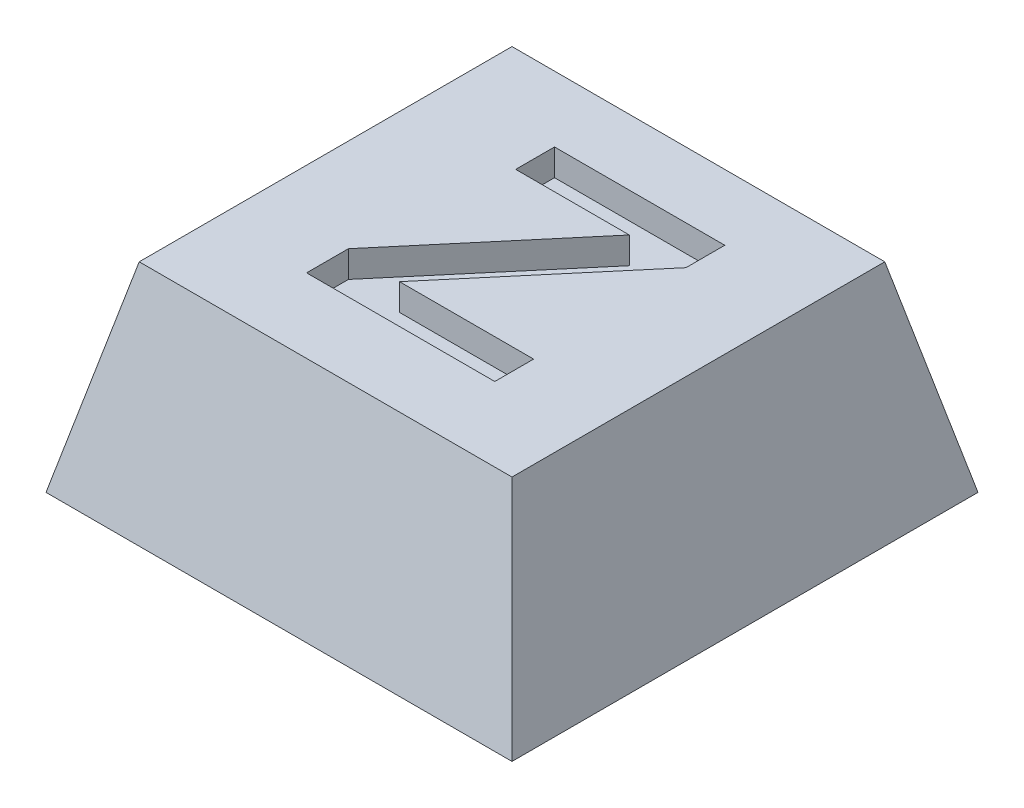
SolidWorks part; units mm, degrees
ref_plane "Front Plane" through (0, 0, 0) normal (0, 0, 1) x (1, 0, 0)
ref_plane "Top Plane" through (0, 0, 0) normal (0, 1, 0) x (1, 0, 0)
ref_plane "Right Plane" through (0, 0, 0) normal (1, 0, 0) x (0, 0, -1)
sketch "Sketch1" plane through (0, 0, 0) normal (0, 1, 0) x (1, 0, 0)
  line L1 (0, 0) -> (7, 0)
  line L2 (0, 0) -> (0, 7)
  line L3 (0, 7) -> (7, 7)
  line L4 (7, 0) -> (7, 7)
  dimension "D1" = 7
  dimension "D2" = 7
extrude "Boss-Extrude1" add sketch "Sketch1" along normal blind 3
sketch "Sketch2" plane through (0, 0, 0) normal (0, 0, 1) x (1, 0, 0)
  line L0 (0, 0) -> (0.7, 3)
  line L1 (0, 3) -> (7, 3) construction
  line L2 (0.7, 3) -> (0, 3)
  line L3 (0, 3) -> (0, 0)
  line L4 (7, 0) -> (6.3, 3)
  line L5 (6.3, 3) -> (7, 3)
  line L6 (7, 3) -> (7, 0)
  dimension "D1" = 0.7
  dimension "D2" = 0.7
extrude "Cut-Extrude1" cut sketch "Sketch2" against normal blind 7
sketch "Sketch3" plane through (0, 0, 0) normal (1, 0, 0) x (0, 0, -1)
  line L0 (0, 0) -> (0.7, 3)
  line L1 (7, 3) -> (0, 3) construction
  line L2 (0.7, 3) -> (0, 3)
  line L3 (0, 3) -> (0, 0)
  line L4 (7, 3) -> (6.3, 3)
  line L5 (6.3, 3) -> (7, 0)
  line L6 (7, 3) -> (7, 0)
  dimension "D1" = 0.7
  dimension "D2" = 0.7
extrude "Cut-Extrude2" cut sketch "Sketch3" along normal blind 11
sketch "Sketch4" plane through (0, 0, 0) normal (0, -1, 0) x (1, 0, 0)
  line L0 (3.5, 0) -> (3.5, -7) construction
  line L1 (0, 0) -> (7, 0) construction
  line L2 (7, -7) -> (0, -7) construction
  line L3 (0, -3.5) -> (7, -3.5) construction
  line L4 (0, -7) -> (0, 0) construction
  line L5 (7, 0) -> (7, -7) construction
  circle A0 centre (3.5, -3.5) radius 1.8
  dimension "D1" = 3.6
extrude "Cut-Extrude3" cut sketch "Sketch4" against normal blind 0.8
sketch "Sketch5" plane through (0, 3, 0) normal (0, 1, 0) x (1, 0, 0)
  text T0 "Z" font "Arial" height 3.5
extrude "Cut-Extrude4" cut sketch "Sketch5" against normal blind 0.4
